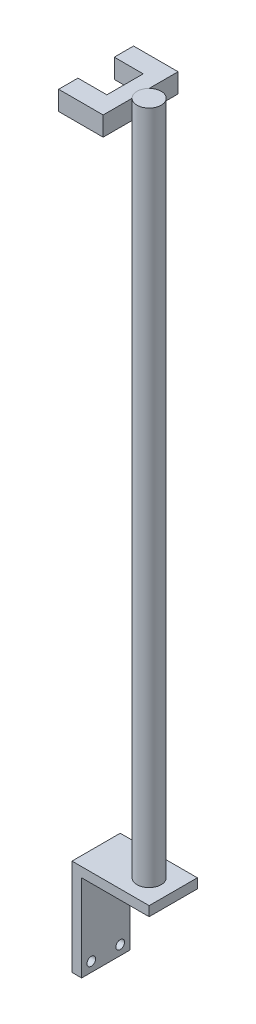
SolidWorks part; units mm, degrees
ref_plane "Płaszczyzna przednia" through (0, 0, 0) normal (0, 0, 1) x (1, 0, 0)
ref_plane "Płaszczyzna górna" through (0, 0, 0) normal (0, 1, 0) x (1, 0, 0)
ref_plane "Płaszczyzna prawa" through (0, 0, 0) normal (1, 0, 0) x (0, 0, -1)
sketch "Szkic1" plane through (0, 0, 0) normal (1, 0, 0) x (0, 0, -1)
  line L1 (0, 0) -> (50, 0)
  line L2 (0, 0) -> (0, 100)
  line L3 (0, 100) -> (50, 100)
  line L4 (50, 0) -> (50, 100)
  circle A0 centre (10, 10) radius 4.5
  circle A1 centre (40, 10) radius 4.5
  dimension "D1" = 9
  dimension "D2" = 9
  dimension "D3" = 50
  dimension "D4" = 100
  dimension "D5" = 10
  dimension "D6" = 10
  dimension "D7" = 10
  dimension "D8" = 10
extrude "Dodanie-wyciągnięcie1" add sketch "Szkic1" along normal blind 10
sketch "Szkic2" plane through (0, 0, -50) normal (0, 0, -1) x (-1, 0, 0)
  line L1 (0, 100) -> (-80, 100)
  line L2 (0, 100) -> (0, 90)
  line L3 (0, 90) -> (-80, 90)
  line L4 (-80, 100) -> (-80, 90)
  dimension "D1" = 10
  dimension "D2" = 80
extrude "Dodanie-wyciągnięcie2" add sketch "Szkic2" against normal blind 50
sketch "Szkic3" plane through (0, 100, 0) normal (0, 1, 0) x (1, 0, 0)
  line L0 (80, 0) -> (80, 50) construction
  line L1 (80, 0) -> (0, 0) construction
  circle A0 centre (55, 25) radius 12.5
  dimension "D1" = 25
  dimension "D2" = 25
  dimension "D3" = 25
extrude "Dodanie-wyciągnięcie3" add sketch "Szkic3" along normal blind 700
sketch "Szkic4" plane through (0, 800, 0) normal (0, 1, 0) x (1, 0, 0)
  line L0 (55, 25) -> (46.1612, 16.1612)
  line L9 (46.1612, 16.1612) -> (46.1612, -13.8388)
  line L10 (46.1612, -13.8388) -> (0, -13.8388)
  line L11 (0, -13.8388) -> (0, 6.1612)
  line L12 (0, 6.1612) -> (30, 6.1612)
  line L13 (30, 6.1612) -> (30, 43.8388)
  line L14 (30, 43.8388) -> (0, 43.8388)
  line L15 (0, 43.8388) -> (0, 63.8388)
  line L16 (0, 63.8388) -> (46.1612, 63.8388)
  line L17 (46.1612, 63.8388) -> (46.1612, 33.8388)
  line L18 (46.1612, 33.8388) -> (55, 25)
  circle A0 centre (55, 25) radius 12.5 construction
  dimension "D1" = 30
  dimension "D2" = 30
  dimension "D3" = 20
  dimension "D4" = 20
  dimension "D5" = 30
extrude "Dodanie-wyciągnięcie4" add sketch "Szkic4" against normal blind 20 separate body
